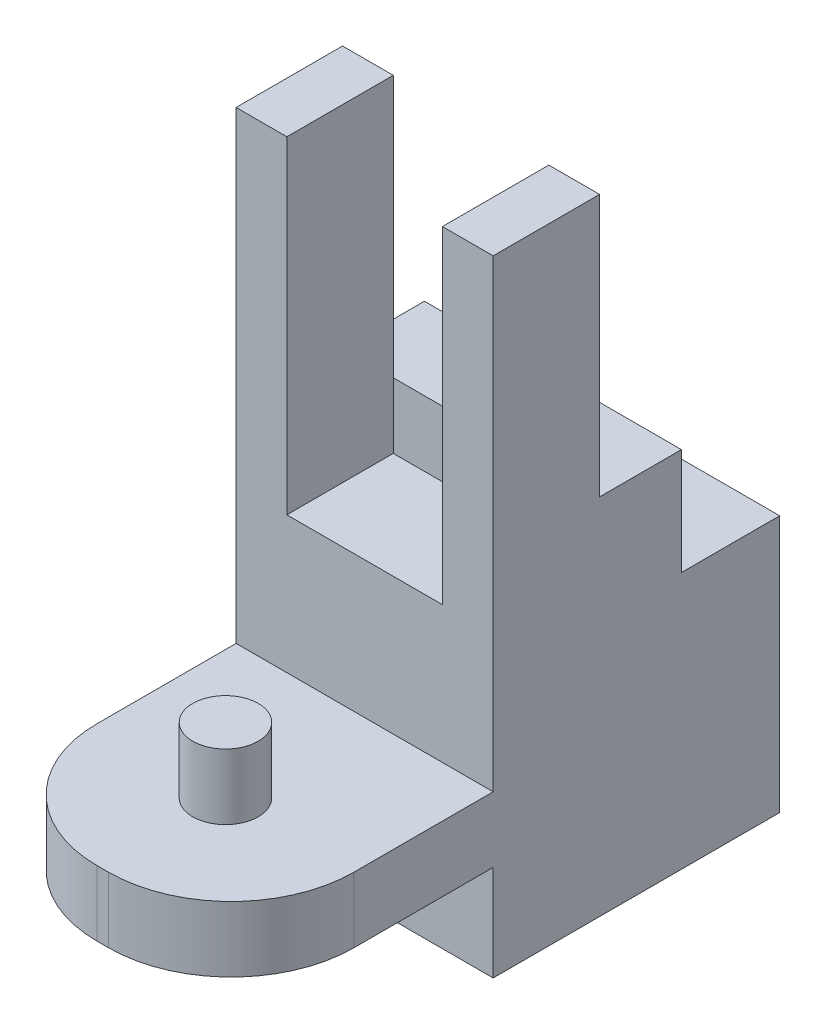
SolidWorks part; units mm, degrees
ref_plane "Front Plane" through (0, 0, 0) normal (0, 0, 1) x (1, 0, 0)
ref_plane "Top Plane" through (0, 0, 0) normal (0, 1, 0) x (1, 0, 0)
ref_plane "Right Plane" through (0, 0, 0) normal (1, 0, 0) x (0, 0, -1)
sketch "Sketch4" plane through (0, 0, 0) normal (0, 0, 1) x (1, 0, 0)
  line L0 (0, 82.063) -> (0, -112.4411) construction
  line L1 (-144.2959, 0) -> (145.5617, 0) construction
  line L2 (-12.7, 12.7) -> (-12.7, -12.7)
  line L3 (-15.7, 15.7) -> (15.7, 15.7)
  line L4 (-15.7, 15.7) -> (-15.7, -15.7)
  line L5 (-15.7, -15.7) -> (15.7, -15.7)
  line L6 (15.7, 15.7) -> (15.7, -15.7)
  line L7 (-12.7, -12.7) -> (12.7, -12.7)
  line L8 (12.7, 12.7) -> (12.7, -12.7)
  line L9 (-12.7, 12.7) -> (12.7, 12.7)
  dimension "D2" = 12.7
  dimension "D3" = 12.7
  dimension "D4" = 12.7
  dimension "D5" = 12.7
  dimension "D1" = 3
extrude "Boss-Extrude3" add sketch "Sketch4" along normal blind 30
sketch "Sketch5" plane through (0, 0, 30) normal (0, 0, 1) x (1, 0, 0)
  line L0 (-15.7, 15.7) -> (15.7, 15.7)
  line L1 (15.7, 15.7) -> (15.7, -15.7)
  line L2 (15.7, -15.7) -> (-15.7, -15.7)
  line L3 (-15.7, -15.7) -> (-15.7, 15.7)
extrude "Boss-Extrude4" add sketch "Sketch5" along normal blind 5
sketch "Sketch6" plane through (0, 0, 35) normal (0, 0, 1) x (1, 0, 0)
  line L0 (-14.6567, 0) -> (15.7, 0) construction
  line L1 (15.7, -15.7) -> (15.7, 15.7) construction
  line L2 (-15.7, 4) -> (15.7, 4)
  line L3 (-15.7, 15.7) -> (-15.7, -15.7) construction
  line L4 (15.7, 4) -> (15.7, -4)
  line L5 (15.7, -4) -> (-15.7, -4)
  line L6 (-15.7, -4) -> (-15.7, 4)
  dimension "D1" = 4
  dimension "D2" = 4
extrude "Boss-Extrude5" add sketch "Sketch6" along normal blind 5
sketch "Sketch7" plane through (0, -4, 0) normal (0, -1, 0) x (1, 0, 0)
  line L0 (-15.7, 40) -> (-15.7, 52)
  line L1 (-0.7, 67) -> (0.7, 67)
  line L2 (15.7, 52) -> (15.7, 40)
  line L3 (-15.7, 40) -> (15.7, 40) construction
  line L4 (15.7, 40) -> (-15.7, 40)
  line L5 (0, 0) -> (0, 92.3619) construction
  arc A0 (0.7, 67) -> (15.7, 52) centre (0.7, 52) cw
  arc A1 (-15.7, 52) -> (-0.7, 67) centre (-0.7, 52) cw
  point P9 (15.7, 67)
  point P12 (-15.7, 67)
  dimension "D3" = 15
  dimension "D1" = 27
  dimension "D2" = 31.4
extrude "Boss-Extrude6" add sketch "Sketch7" against normal blind 8
sketch "Sketch8" plane through (0, -4, 0) normal (0, -1, 0) x (1, 0, 0)
  line L0 (0, 67.4318) -> (0, -5.9603) construction
  line L1 (0.7, 67) -> (-0.7, 67) construction
  circle A0 centre (0, 52) radius 4
  dimension "D1" = 15
extrude "Boss-Extrude7" add sketch "Sketch8" along normal blind 8
mirror "Mirror1" about plane through (0, 0, 0) normal (0, 1, 0) of "Boss-Extrude7"
sketch "Sketch9" plane through (0, 15.7, 0) normal (0, 1, 0) x (1, 0, 0)
  line L1 (-15.7, -32) -> (15.7, -32)
  line L2 (-15.7, -35) -> (-15.7, 0) construction
  line L3 (15.7, -35) -> (15.7, 0) construction
  line L4 (0, 15.8647) -> (0, -78.6922) construction
  line L5 (0, -52) -> (31.7707, -52) construction
  line L6 (31.7707, -52) -> (-30.9902, -52) construction
  line L7 (-15.7, -32) -> (-15.7, -22)
  line L8 (-15.7, -22) -> (15.7, -22)
  line L9 (15.7, -22) -> (15.7, -32)
  dimension "D1" = 20
  dimension "D2" = 10
extrude "Boss-Extrude8" add sketch "Sketch9" along normal blind 5
sketch "Sketch10" plane through (0, 15.7, 0) normal (0, 1, 0) x (1, 0, 0)
  line L0 (-15.7, -22) -> (-15.7, -12)
  line L1 (-15.7, -22) -> (-15.7, 0) construction
  line L2 (-15.7, -12) -> (15.7, -12)
  line L3 (15.7, -22) -> (15.7, 0) construction
  line L4 (15.7, -12) -> (15.7, -22)
  line L5 (15.7, -22) -> (-15.7, -22)
  dimension "D1" = 10
extrude "Boss-Extrude9" add sketch "Sketch10" along normal blind 13
sketch "Sketch11" plane through (0, 20.7, 0) normal (0, 1, 0) x (1, 0, 0)
  line L0 (-15.7, -22) -> (-9.5, -22)
  line L1 (15.7, -22) -> (-15.7, -22) construction
  line L2 (-9.5, -22) -> (-9.5, -32)
  line L3 (-15.7, -32) -> (15.7, -32) construction
  line L4 (-9.5, -32) -> (-15.7, -32)
  line L5 (-15.7, -32) -> (-15.7, -22)
  line L6 (9.5, -22) -> (9.5, -32)
  line L7 (-15.7, -22) -> (15.7, -22) construction
  line L8 (-15.7, -32) -> (15.7, -32) construction
  line L9 (9.5, -32) -> (15.7, -32)
  line L10 (15.7, -32) -> (15.7, -22)
  line L11 (15.7, -32) -> (15.7, -22) construction
  line L12 (15.7, -22) -> (9.5, -22)
  dimension "D1" = 6.2
  dimension "D2" = 6.2
extrude "Boss-Extrude10" add sketch "Sketch11" along normal blind 40
sketch "Sketch12" plane through (0, 0, 32) normal (0, 0, 1) x (1, 0, 0)
  line L0 (-15.7, 60.7) -> (-9.5, 60.7)
  line L1 (-9.5, 60.7) -> (-9.5, 20.7)
  line L2 (-9.5, 20.7) -> (9.5, 20.7)
  line L3 (9.5, 20.7) -> (9.5, 60.7)
  line L4 (9.5, 60.7) -> (15.7, 60.7)
  line L5 (15.7, 60.7) -> (15.7, 15.7)
  line L6 (15.7, 15.7) -> (-15.7, 15.7)
  line L7 (-15.7, 15.7) -> (-15.7, 60.7)
extrude "Boss-Extrude11" add sketch "Sketch12" along normal blind 3
